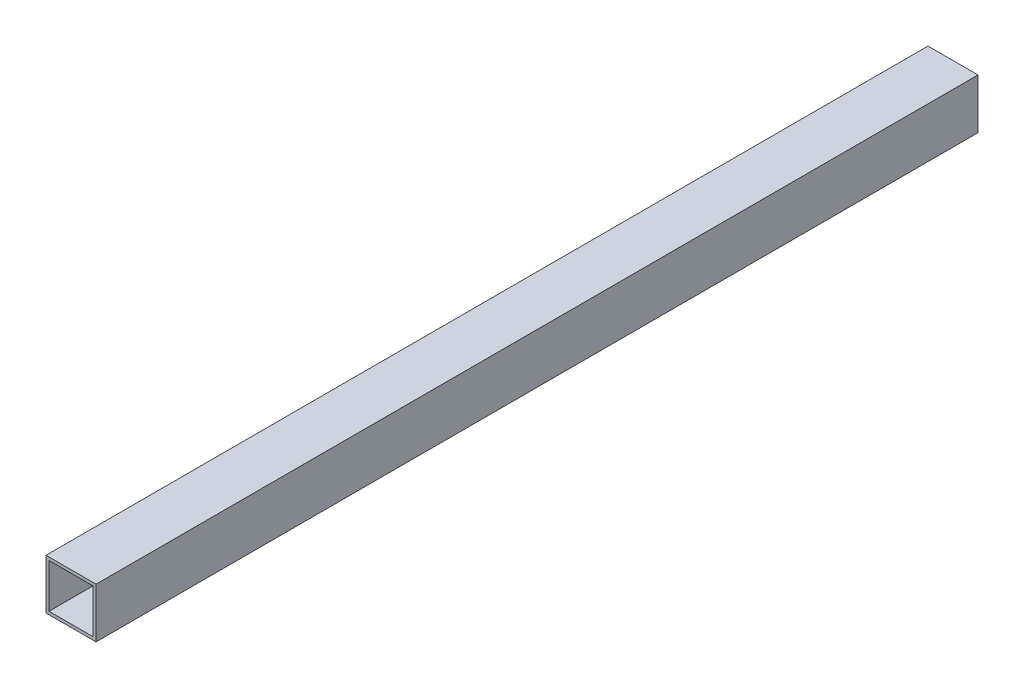
SolidWorks part; units mm, degrees
ref_plane "Front Plane" through (0, 0, 0) normal (0, 0, 1) x (1, 0, 0)
ref_plane "Top Plane" through (0, 0, 0) normal (0, 1, 0) x (1, 0, 0)
ref_plane "Right Plane" through (0, 0, 0) normal (1, 0, 0) x (0, 0, -1)
sketch "Sketch1" plane through (0, 0, 0) normal (0, 0, 1) x (1, 0, 0)
  line L1 (0, 0) -> (-25.4, 0)
  line L2 (0, 0) -> (0, 25.4)
  line L3 (0, 25.4) -> (-25.4, 25.4)
  line L4 (-25.4, 0) -> (-25.4, 25.4)
  dimension "D1" = 25.4
  dimension "D2" = 25.4
extrude "Extrude-Thin1" add sketch "Sketch1" along normal blind 447.675 thin
